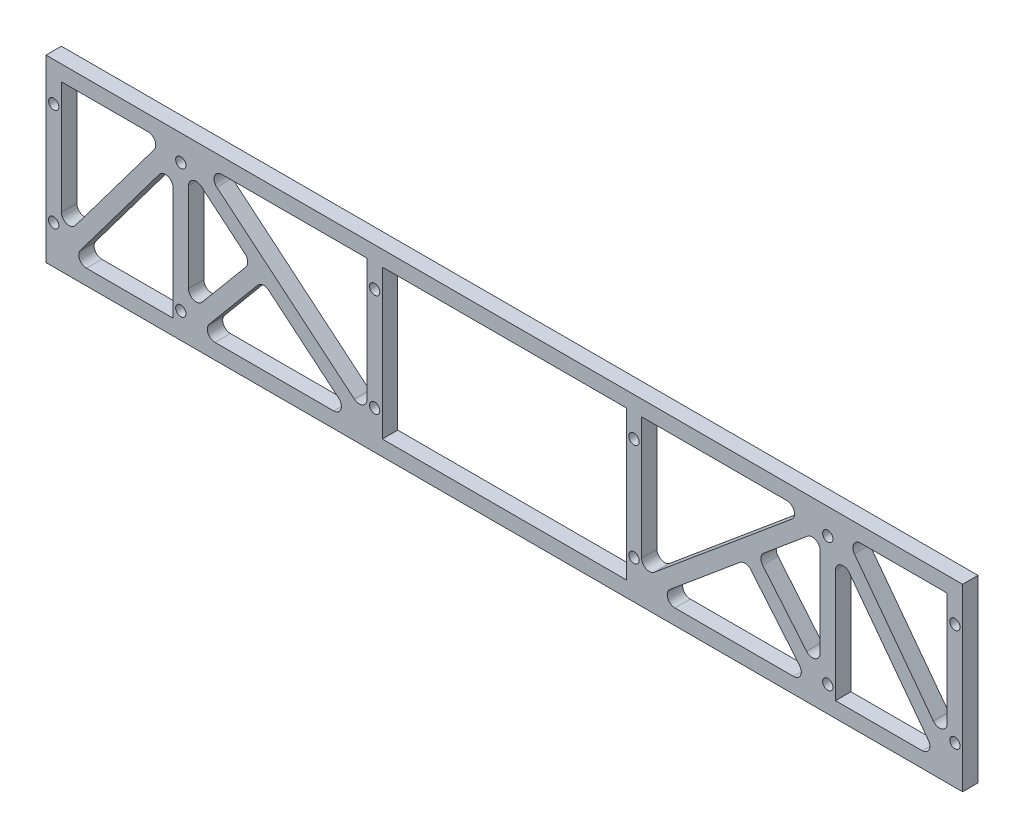
SolidWorks part; units mm, degrees
ref_plane "前视基准面" through (0, 0, 0) normal (0, 0, 1) x (1, 0, 0)
ref_plane "上视基准面" through (0, 0, 0) normal (0, 1, 0) x (1, 0, 0)
ref_plane "右视基准面" through (0, 0, 0) normal (1, 0, 0) x (0, 0, -1)
sketch "草图2" plane through (0, 0, 0) normal (0, 0, 1) x (1, 0, 0)
  line L1 (-178.5, -35) -> (178.5, -35)
  line L2 (-178.5, -35) -> (-178.5, 35)
  line L3 (-178.5, 35) -> (178.5, 35)
  line L4 (178.5, -35) -> (178.5, 35)
  line L5 (-178.5, -35) -> (178.5, 35) construction
  line L6 (-178.5, 35) -> (178.5, -35) construction
  line L7 (-172.5, -29) -> (172.5, -29)
  line L8 (-172.5, -29) -> (-172.5, 29)
  line L9 (-172.5, 29) -> (172.5, 29)
  line L10 (172.5, -29) -> (172.5, 29)
  line L11 (-172.5, -29) -> (172.5, 29) construction
  line L12 (-172.5, 29) -> (172.5, -29) construction
  point P0 (0, 0)
  point P6 (0, 0)
  dimension "D1" = 357
  dimension "D2" = 70
  dimension "D3" = 345
  dimension "D4" = 58
extrude "凸台-拉伸1" add sketch "草图2" along normal blind 6
sketch "草图3" plane through (0, 0, 0) normal (0, 0, 1) x (1, 0, 0)
  line L0 (0, -1000) -> (0, 49000) construction
  line L1 (172.5, 29) -> (-172.5, 29) construction
  line L2 (-129, 29) -> (-123, 29)
  line L3 (-129, 29) -> (-129, -29)
  line L4 (-129, -29) -> (-123, -29)
  line L5 (-123, 29) -> (-123, -29)
  line L6 (-172.5, -29) -> (172.5, -29) construction
  line L8 (129, -29) -> (123, -29)
  line L9 (123, 29) -> (123, -29)
  line L10 (129, 29) -> (123, 29)
  line L11 (129, 29) -> (129, -29)
  dimension "D1" = 123
  dimension "D2" = 6
extrude "凸台-拉伸2" add sketch "草图3" along normal blind 6
sketch "草图4" plane through (0, 0, 0) normal (0, 0, 1) x (1, 0, 0)
  line L0 (-172.5, -29) -> (-129, 29) construction
  line L1 (0, -1000) -> (0, 49000) construction
  line L12 (-172.5, -29) -> (-172.5, -24)
  line L13 (-172.5, 29) -> (-172.5, -29) construction
  line L14 (-172.5, -24) -> (-132.75, 29)
  line L15 (-129, 29) -> (-172.5, 29) construction
  line L16 (-132.75, 29) -> (-129, 29)
  line L17 (-129, 29) -> (-129, 24)
  line L18 (-129, 29) -> (-129, -29) construction
  line L19 (-129, 24) -> (-168.75, -29)
  line L20 (-172.5, -29) -> (-129, -29) construction
  line L21 (-168.75, -29) -> (-172.5, -29)
  line L22 (129, 24) -> (168.75, -29)
  line L23 (129, 29) -> (129, 24)
  line L24 (132.75, 29) -> (129, 29)
  line L25 (172.5, -24) -> (132.75, 29)
  line L26 (172.5, -29) -> (172.5, -24)
  line L27 (168.75, -29) -> (172.5, -29)
  dimension "D1" = 3
  dimension "D2" = 3
extrude "凸台-拉伸3" add sketch "草图4" along normal blind 6
fillet "圆角1" radius 3 8 edges at (172.5, -24, 3) (168.75, -29, 3) (132.75, 29, 3) (129, 24, 3) (-129, 24, 3) (-168.75, -29, 3) (-172.5, -24, 3) (-132.75, 29, 3)
sketch "草图5" plane through (0, 0, 0) normal (0, 0, 1) x (1, 0, 0)
  line L0 (0, -1000) -> (0, 49000) construction
  line L1 (123, 29) -> (-123, 29) construction
  line L2 (53.5, 29) -> (47.5, 29)
  line L3 (53.5, 29) -> (53.5, -29)
  line L4 (53.5, -29) -> (47.5, -29)
  line L5 (47.5, 29) -> (47.5, -29)
  line L6 (-123, -29) -> (123, -29) construction
  line L8 (-53.5, -29) -> (-47.5, -29)
  line L9 (-47.5, 29) -> (-47.5, -29)
  line L10 (-53.5, 29) -> (-47.5, 29)
  line L11 (-53.5, 29) -> (-53.5, -29)
  dimension "D1" = 6
  dimension "D2" = 47.5
extrude "凸台-拉伸4" add sketch "草图5" along normal blind 6
sketch "草图6" plane through (0, 0, 0) normal (0, 0, 1) x (1, 0, 0)
  line L0 (0, -1000) -> (0, 49000) construction
  line L1 (123, 29) -> (53.5, -29) construction
  line L2 (123, 29) -> (123, 25.0926)
  line L3 (123, 29) -> (123, -29) construction
  line L4 (123, 25.0926) -> (98.6935, 4.808)
  line L5 (53.5, -29) -> (123, -29) construction
  line L6 (58.1822, -29) -> (53.5, -29)
  line L7 (53.5, -29) -> (53.5, -25.0926)
  line L8 (53.5, -29) -> (53.5, 29) construction
  line L9 (53.5, -25.0926) -> (118.3178, 29)
  line L10 (123, 29) -> (53.5, 29) construction
  line L11 (118.3178, 29) -> (123, 29)
  line L12 (123, -29) -> (96.3902, 2.8859) construction
  line L13 (123, -29) -> (123, -24.3178)
  line L14 (123, -24.3178) -> (98.6935, 4.808)
  line L15 (123, -29) -> (119.0926, -29)
  line L16 (119.0926, -29) -> (94.0869, 0.9637)
  line L17 (94.0869, 0.9637) -> (58.1822, -29)
  line L18 (-119.0926, -29) -> (-94.0869, 0.9637)
  line L19 (-123, -29) -> (-119.0926, -29)
  line L20 (-123, -29) -> (-123, -24.3178)
  line L21 (-123, -24.3178) -> (-98.6935, 4.808)
  line L22 (-123, 25.0926) -> (-98.6935, 4.808)
  line L23 (-123, 29) -> (-123, 25.0926)
  line L24 (-118.3178, 29) -> (-123, 29)
  line L25 (-53.5, -25.0926) -> (-118.3178, 29)
  line L26 (-53.5, -29) -> (-53.5, -25.0926)
  line L27 (-58.1822, -29) -> (-53.5, -29)
  line L28 (-94.0869, 0.9637) -> (-58.1822, -29)
  dimension "D1" = 3
  dimension "D2" = 3
  dimension "D3" = 3
  dimension "D4" = 3
extrude "凸台-拉伸5" add sketch "草图6" along normal blind 6
fillet "圆角2" radius 3 16 edges at (-53.5, -25.0926, 3) (-58.1822, -29, 3) (-119.0926, -29, 3) (-94.0869, 0.9637, 3) (-98.6935, 4.808, 3) (-123, -24.3178, 3) (-123, 25.0926, 3) (-118.3178, 29, 3) (118.3178, 29, 3) (53.5, -25.0926, 3) (58.1822, -29, 3) (119.0926, -29, 3) (94.0869, 0.9637, 3) (98.6935, 4.808, 3) (123, -24.3178, 3) (123, 25.0926, 3)
sketch "草图7" plane through (0, 0, 0) normal (0, 0, -1) x (-1, 0, 0)
  line L0 (0, -1000) -> (0, 49000) construction
  line L1 (178.5, 35) -> (178.5, -35) construction
  line L2 (47.5, -29) -> (47.5, 29) construction
  line L3 (129, 15) -> (129, -29) construction
  circle A0 centre (175.5, 20) radius 2
  circle A1 centre (175.5, -20) radius 2
  circle A2 centre (50.5, 20) radius 2
  circle A3 centre (50.5, -20) radius 2
  circle A4 centre (-175.5, -20) radius 2
  circle A5 centre (-175.5, 20) radius 2
  circle A6 centre (-50.5, -20) radius 2
  circle A7 centre (-50.5, 20) radius 2
  circle A8 centre (126, 25) radius 2
  circle A9 centre (126, -25) radius 2
  circle A10 centre (-126, -25) radius 2
  circle A11 centre (-126, 25) radius 2
  dimension "D1" = 4
  dimension "D2" = 4
  dimension "D3" = 4
  dimension "D4" = 4
  dimension "D5" = 3
  dimension "D6" = 3
  dimension "D7" = 3
  dimension "D8" = 3
  dimension "D9" = 20
  dimension "D10" = 20
  dimension "D11" = 20
  dimension "D12" = 20
  dimension "D13" = 4
  dimension "D14" = 4
  dimension "D15" = 3
  dimension "D16" = 3
  dimension "D17" = 25
  dimension "D18" = 25
extrude "切除-拉伸1" cut sketch "草图7" against normal blind 6
